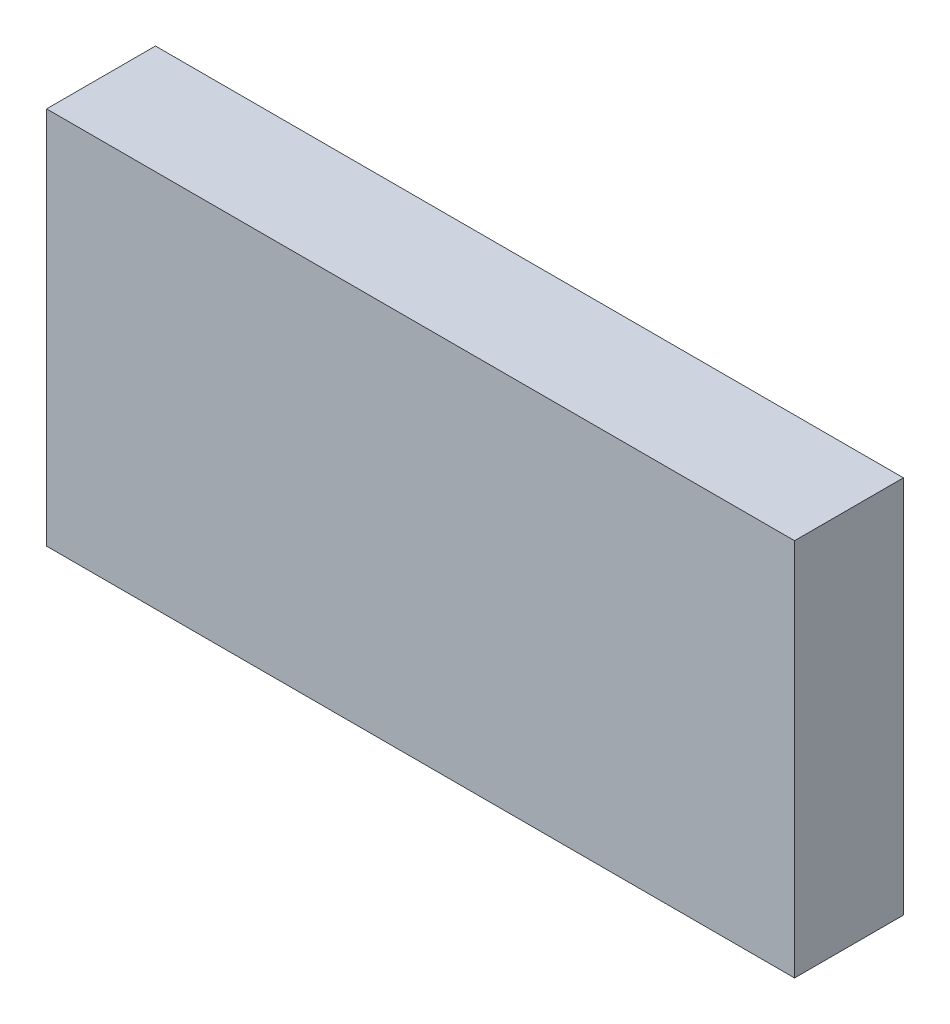
SolidWorks part; units mm, degrees
ref_plane "Front Plane" through (0, 0, 0) normal (0, 0, 1) x (1, 0, 0)
ref_plane "Top Plane" through (0, 0, 0) normal (0, 1, 0) x (1, 0, 0)
ref_plane "Right Plane" through (0, 0, 0) normal (1, 0, 0) x (0, 0, -1)
sketch "Sketch1" plane through (0, 0, 0) normal (0, 0, 1) x (1, 0, 0)
  line L1 (-62.7063, -31.75) -> (62.7062, -31.75)
  line L2 (-62.7063, -31.75) -> (-62.7063, 31.75)
  line L3 (-62.7063, 31.75) -> (62.7062, 31.75)
  line L4 (62.7062, -31.75) -> (62.7062, 31.75)
  line L5 (-62.7063, -31.75) -> (62.7062, 31.75) construction
  line L6 (-62.7063, 31.75) -> (62.7062, -31.75) construction
  point P0 (0, 0)
  dimension "D1" = 125.4125
  dimension "D2" = 63.5
extrude "Boss-Extrude1" add sketch "Sketch1" along normal mid plane 18.2562
